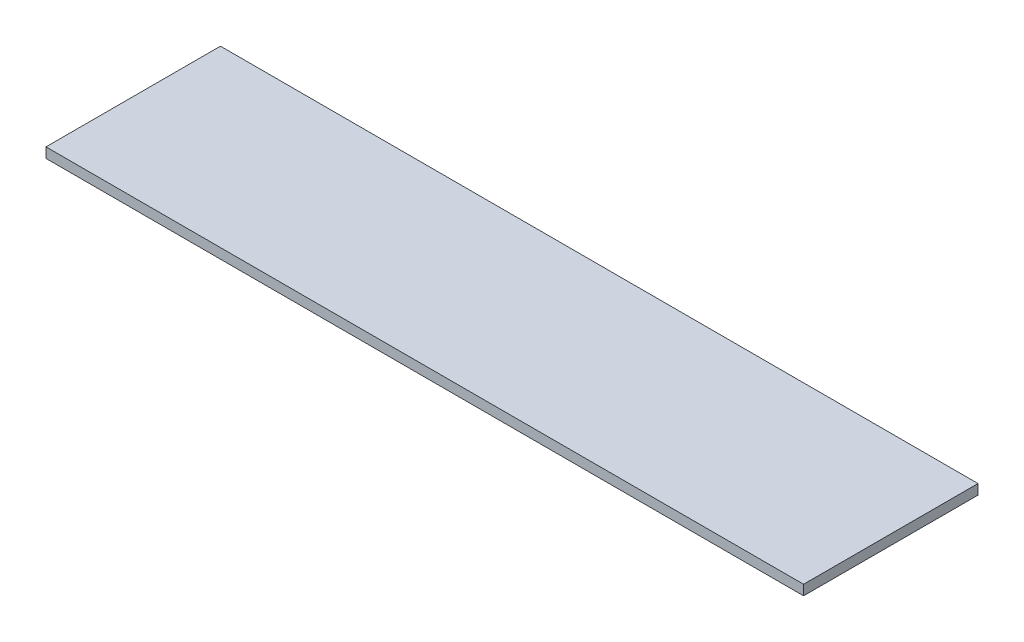
SolidWorks part; units mm, degrees
ref_plane "Front Plane" through (0, 0, 0) normal (0, 0, 1) x (1, 0, 0)
ref_plane "Top Plane" through (0, 0, 0) normal (0, 1, 0) x (1, 0, 0)
ref_plane "Right Plane" through (0, 0, 0) normal (1, 0, 0) x (0, 0, -1)
sketch "Sketch1" plane through (0, 0, 0) normal (0, 1, 0) x (1, 0, 0)
  line L5 (-75.35, 17.35) -> (75.35, 17.35)
  line L6 (-75.35, 17.35) -> (-75.35, -17.35)
  line L7 (-75.35, -17.35) -> (75.35, -17.35)
  line L8 (75.35, 17.35) -> (75.35, -17.35)
  line L9 (-75.35, 17.35) -> (75.35, -17.35) construction
  line L10 (-75.35, -17.35) -> (75.35, 17.35) construction
  point P0 (0, 0)
  dimension "D1" = 150.7
  dimension "D2" = 34.7
extrude "Boss-Extrude1" add sketch "Sketch1" along normal blind 2
